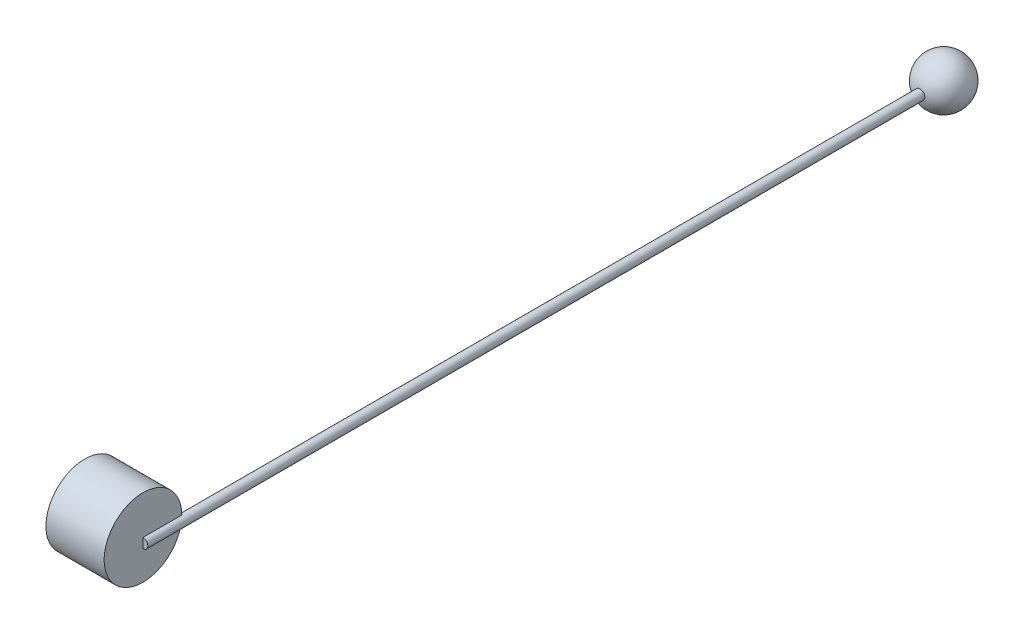
SolidWorks part; units mm, degrees
ref_plane "Plano frontal" through (0, 0, 0) normal (1, 0, 0) x (0, 1, 0)
ref_plane "Plano superior" through (0, 0, 0) normal (0, 0, 1) x (0, 1, 0)
ref_plane "Plano direito" through (0, 0, 0) normal (0, 1, 0) x (-1, 0, 0)
sketch "Esboço3" plane through (0, 0, 0) normal (0, 1, 0) x (-1, 0, 0)
  line L0 (0, 0) -> (0, -80) construction
  line L1 (0, -80) -> (0, -85)
  arc A0 (0, -85) -> (0, -80) centre (0, -82.5) ccw
revolve "Revolução1" add sketch "Esboço3" angle 360 about L1
sketch "Esboço4" plane through (0, 0, 0) normal (0, 0, 1) x (0, 1, 0)
  circle A0 centre (0, 0) radius 0.5
extrude "Ressalto-extrusão1" add sketch "Esboço4" against normal up to body
sketch3d "SMLINK_PSI_AXIS"
  line L0 (-25, 0, 0) -> (25, 0, 0) construction
  point P0 (0, 0, 0)
ref_plane "SMLINK_PSI_PLANE" through (0, 0, 0) normal (1, 0, 0) x (0, 0, -1)
sketch "SMLINK_PSI_CIRCLE" plane through (0, 0, 0) normal (1, 0, 0) x (0, 0, -1)
  circle A0 centre (0, 0.5) radius 4
extrude "SMLINK_PSI_CYLINDER" add sketch "SMLINK_PSI_CIRCLE" against normal blind 6 separate body
